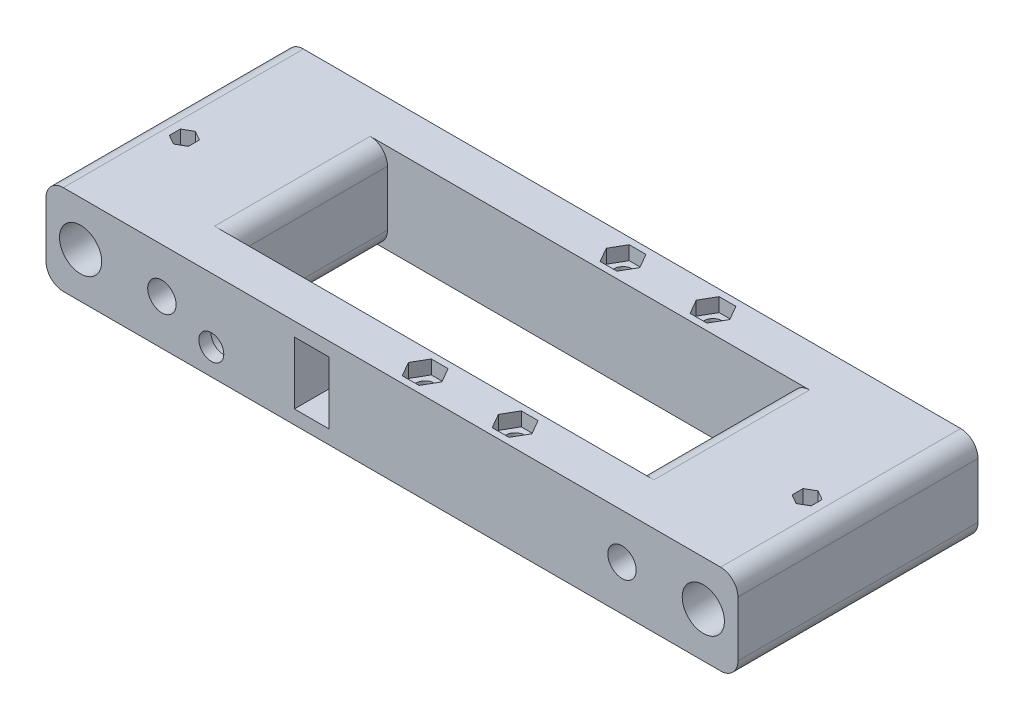
SolidWorks part; units mm, degrees
ref_plane "Front Plane" through (0, 0, 0) normal (0, 0, 1) x (1, 0, 0)
ref_plane "Top Plane" through (0, 0, 0) normal (0, 1, 0) x (1, 0, 0)
ref_plane "Right Plane" through (0, 0, 0) normal (1, 0, 0) x (0, 0, -1)
sketch "Sketch1" plane through (0, 0, 0) normal (0, 0, 1) x (1, 0, 0)
  line L0 (-58.5, 26) -> (-58.5, 0) construction
  line L1 (0, 0) -> (-100, 0)
  line L2 (0, 0) -> (0, 26)
  line L3 (0, 26) -> (-100, 26)
  line L4 (-100, 0) -> (-100, 26)
  circle A0 centre (-90, 13) radius 6.1
  circle A1 centre (-66.5, 13) radius 4.1
  point P9 (-100, 13)
  dimension "D3" = 12.2
  dimension "D4" = 8.2
  dimension "D1" = 100
  dimension "D2" = 26
  dimension "D5" = 23.5
  dimension "D6" = 10
  dimension "D7" = 8
  dimension "D8" = 41.5
extrude "Boss-Extrude1" add sketch "Sketch1" along normal blind 40
sketch "Sketch2" plane through (0, 0, 0) normal (0, 0, -1) x (-1, 0, 0)
  line L1 (100, 26) -> (0, 26)
  line L2 (100, 26) -> (100, 0)
  line L3 (100, 0) -> (0, 0)
  line L4 (0, 26) -> (0, 0)
extrude "Boss-Extrude2" add sketch "Sketch2" along normal blind 29.4
sketch "Sketch3" plane through (0, 26, 0) normal (0, 1, 0) x (1, 0, 0)
  line L0 (0, -40) -> (0, 29.4) construction
  line L1 (0, 17.2) -> (-58.5, 17.2)
  line L2 (0, 17.2) -> (0, -27.8)
  line L3 (0, -27.8) -> (-58.5, -27.8)
  line L4 (-58.5, 17.2) -> (-58.5, -27.8)
  line L5 (-100, -40) -> (-100, 29.4) construction
  line L6 (-100, 29.4) -> (0, 29.4) construction
  line L7 (0, -40) -> (-100, -40) construction
  dimension "D1" = 41.5
  dimension "D2" = 12.2
  dimension "D3" = 12.2
extrude "Cut-Extrude1" cut sketch "Sketch3" against normal up to next
mirror "Mirror2" about plane through (0, 0, 40) normal (-1, 0, 0) of "Boss-Extrude2", "Cut-Extrude1", "Boss-Extrude1"
sketch "Sketch4" plane through (0, 26, 0) normal (0, 1, 0) x (1, 0, 0)
  line L0 (-100, 29.4) -> (100, 29.4) construction
  line L1 (-5.5, 29.4) -> (-5.5, 17.2) construction
  line L2 (58.5, 17.2) -> (-58.5, 17.2) construction
  line L3 (58.5, 17.2) -> (58.5, -27.8) construction
  circle A0 centre (3.5, 23.3) radius 2.6
  circle A1 centre (29.5, 23.3) radius 2.6
  dimension "D1" = 6.1
  dimension "D3" = 9
  dimension "D4" = 26
  dimension "D5" = 5.2
  dimension "D2" = 64
extrude "Cut-Extrude2" cut sketch "Sketch4" against normal through all
sketch "Sketch5" plane through (0, 0, 0) normal (0, -1, 0) x (1, 0, 0)
  line L1 (34.2343, -23.3) -> (31.8671, -19.2)
  line L2 (31.8671, -19.2) -> (27.1329, -19.2)
  line L3 (27.1329, -19.2) -> (24.7657, -23.3)
  line L4 (24.7657, -23.3) -> (27.1329, -27.4)
  line L5 (27.1329, -27.4) -> (31.8671, -27.4)
  line L6 (31.8671, -27.4) -> (34.2343, -23.3)
  line L7 (-1.2343, -23.3) -> (1.1329, -27.4)
  line L8 (1.1329, -27.4) -> (5.8671, -27.4)
  line L9 (5.8671, -27.4) -> (8.2343, -23.3)
  line L10 (8.2343, -23.3) -> (5.8671, -19.2)
  line L11 (5.8671, -19.2) -> (1.1329, -19.2)
  line L12 (1.1329, -19.2) -> (-1.2343, -23.3)
  circle A0 centre (29.5, -23.3) radius 4.1 construction
  circle A1 centre (3.5, -23.3) radius 4.1 construction
  dimension "D1" = 8.2
  dimension "D2" = 8.2
extrude "Cut-Extrude3" cut sketch "Sketch5" against normal blind 4
ref_plane "Plane1" through (0, 0, 5.3) normal (0, 0, 1) x (1, 0, 0)
mirror "Mirror3" about plane through (0, 0, 5.3) normal (0, 0, 1) of "Cut-Extrude3", "Cut-Extrude2"
sketch "Sketch6" plane through (0, 0, 40) normal (0, 0, 1) x (1, 0, 0)
  line L0 (-8.1, 26) -> (-8.1, 0) construction
  line L1 (100, 26) -> (-100, 26) construction
  line L2 (-100, 0) -> (100, 0) construction
  line L3 (0.9, 26) -> (0.9, 4) construction
  line L4 (-100, 26) -> (-100, 0) construction
  line L5 (-18.2, 22) -> (-28.2, 22)
  line L6 (-18.2, 22) -> (-18.2, 4)
  line L7 (-18.2, 4) -> (-28.2, 4)
  line L8 (-28.2, 22) -> (-28.2, 4)
  point P12 (-28.2, 13)
  point P15 (-100, 13)
  dimension "D1" = 9
  dimension "D2" = 10.1
  dimension "D3" = 10
  dimension "D4" = 18
extrude "Cut-Extrude4" cut sketch "Sketch6" against normal up to vertex
fillet "Fillet1" radius 5 8 edges at (58.5, 26, 5.3) (58.5, 0, 5.3) (-58.5, 0, 5.3) (100, 0, 5.3) (100, 26, 5.3) (-100, 0, 5.3) (-100, 26, 5.3) (-58.5, 26, 5.3)
sketch "Sketch7" plane through (0, 26, 0) normal (0, 1, 0) x (1, 0, 0)
  line L0 (63.5, 17.2) -> (-63.5, 17.2) construction
  line L1 (8.3497, 23.3) -> (5.9249, 27.5)
  line L2 (5.9249, 27.5) -> (1.0751, 27.5)
  line L3 (1.0751, 27.5) -> (-1.3497, 23.3)
  line L4 (-1.3497, 23.3) -> (1.0751, 19.1)
  line L5 (1.0751, 19.1) -> (5.9249, 19.1)
  line L6 (5.9249, 19.1) -> (8.3497, 23.3)
  line L7 (34.3497, 23.3) -> (31.9249, 27.5)
  line L8 (31.9249, 27.5) -> (27.0751, 27.5)
  line L9 (27.0751, 27.5) -> (24.6503, 23.3)
  line L10 (24.6503, 23.3) -> (27.0751, 19.1)
  line L11 (27.0751, 19.1) -> (31.9249, 19.1)
  line L12 (31.9249, 19.1) -> (34.3497, 23.3)
  circle A0 centre (3.5, 23.3) radius 4.2 construction
  circle A1 centre (29.5, 23.3) radius 4.2 construction
  point P20 (29.5, 19.1)
  dimension "D1" = 8.4
  dimension "D2" = 8.4
extrude "Cut-Extrude5" cut sketch "Sketch7" against normal blind 4
mirror "Mirror4" about plane through (0, 0, 5.3) normal (0, 0, 1) of "Cut-Extrude5"
sketch "Sketch8" plane through (0, 4, 0) normal (0, -1, 0) x (1, 0, 0)
  line L0 (27.1329, 38) -> (31.8671, 38) construction
  line L1 (31.8671, 38) -> (34.2343, 33.9) construction
  line L2 (34.2343, 33.9) -> (31.8671, 29.8) construction
  line L3 (31.8671, 29.8) -> (27.1329, 29.8) construction
  line L4 (27.1329, 29.8) -> (24.7657, 33.9) construction
  line L5 (24.7657, 33.9) -> (27.1329, 38) construction
  line L6 (1.1329, 38) -> (5.8671, 38) construction
  line L7 (5.8671, 38) -> (8.2343, 33.9) construction
  line L8 (8.2343, 33.9) -> (5.8671, 29.8) construction
  line L9 (5.8671, 29.8) -> (1.1329, 29.8) construction
  line L10 (1.1329, 29.8) -> (-1.2343, 33.9) construction
  line L11 (-1.2343, 33.9) -> (1.1329, 38) construction
  line L12 (27.1329, 38) -> (31.8671, 38)
  line L13 (31.8671, 38) -> (34.2343, 33.9)
  line L14 (34.2343, 33.9) -> (31.8671, 29.8)
  line L15 (31.8671, 29.8) -> (27.1329, 29.8)
  line L16 (27.1329, 29.8) -> (24.7657, 33.9)
  line L17 (24.7657, 33.9) -> (27.1329, 38)
  line L18 (1.1329, 38) -> (5.8671, 38)
  line L19 (5.8671, 38) -> (8.2343, 33.9)
  line L20 (8.2343, 33.9) -> (5.8671, 29.8)
  line L21 (5.8671, 29.8) -> (1.1329, 29.8)
  line L22 (1.1329, 29.8) -> (-1.2343, 33.9)
  line L23 (-1.2343, 33.9) -> (1.1329, 38)
  circle A0 centre (3.5, 33.9) radius 2.6 construction
  circle A1 centre (29.5, 33.9) radius 2.6 construction
  circle A2 centre (3.5, 33.9) radius 2.6
  circle A3 centre (29.5, 33.9) radius 2.6
extrude "Boss-Extrude3" add sketch "Sketch8" along normal up to surface (4 mm away) up to face at (3.5, 0, 33.9)
sketch "Sketch9" plane through (0, 4, 0) normal (0, -1, 0) x (1, 0, 0)
  line L0 (31.8671, -19.2) -> (27.1329, -19.2) construction
  line L1 (34.2343, -23.3) -> (31.8671, -19.2) construction
  line L2 (31.8671, -27.4) -> (34.2343, -23.3) construction
  line L3 (27.1329, -27.4) -> (31.8671, -27.4) construction
  line L4 (24.7657, -23.3) -> (27.1329, -27.4) construction
  line L5 (27.1329, -19.2) -> (24.7657, -23.3) construction
  line L6 (1.1329, -19.2) -> (-1.2343, -23.3) construction
  line L7 (5.8671, -19.2) -> (1.1329, -19.2) construction
  line L8 (8.2343, -23.3) -> (5.8671, -19.2) construction
  line L9 (5.8671, -27.4) -> (8.2343, -23.3) construction
  line L10 (1.1329, -27.4) -> (5.8671, -27.4) construction
  line L11 (-1.2343, -23.3) -> (1.1329, -27.4) construction
  line L12 (31.8671, -19.2) -> (27.1329, -19.2)
  line L13 (34.2343, -23.3) -> (31.8671, -19.2)
  line L14 (31.8671, -27.4) -> (34.2343, -23.3)
  line L15 (27.1329, -27.4) -> (31.8671, -27.4)
  line L16 (24.7657, -23.3) -> (27.1329, -27.4)
  line L17 (27.1329, -19.2) -> (24.7657, -23.3)
  line L18 (1.1329, -19.2) -> (-1.2343, -23.3)
  line L19 (5.8671, -19.2) -> (1.1329, -19.2)
  line L20 (8.2343, -23.3) -> (5.8671, -19.2)
  line L21 (5.8671, -27.4) -> (8.2343, -23.3)
  line L22 (1.1329, -27.4) -> (5.8671, -27.4)
  line L23 (-1.2343, -23.3) -> (1.1329, -27.4)
  circle A0 centre (3.5, -23.3) radius 2.6 construction
  circle A1 centre (29.5, -23.3) radius 2.6 construction
  circle A2 centre (3.5, -23.3) radius 2.6
  circle A3 centre (29.5, -23.3) radius 2.6
extrude "Boss-Extrude4" add sketch "Sketch9" along normal up to surface (4 mm away) up to face at (29.5, 0, -23.3)
sketch "Sketch10" plane through (0, 0, 0) normal (0, -1, 0) x (1, 0, 0)
  line L1 (-96.1, 0) -> (-83.9, 0) construction
  line L2 (83.9, 0) -> (96.1, 0) construction
  circle A0 centre (-90, 10) radius 1.5
  circle A1 centre (90, 10) radius 1.5
  point P5 (-90, 0)
  point P14 (90, 0)
  dimension "D3" = 3
  dimension "D4" = 3
  dimension "D1" = 10
  dimension "D2" = 10
extrude "Cut-Extrude6" cut sketch "Sketch10" against normal through all
sketch "Sketch11" plane through (0, 26, 0) normal (0, 1, 0) x (1, 0, 0)
  line L0 (-95, 29.4) -> (-95, -40) construction
  line L1 (-90, -13.1754) -> (-87.25, -11.5877)
  line L2 (-87.25, -11.5877) -> (-87.25, -8.4123)
  line L3 (-87.25, -8.4123) -> (-90, -6.8246)
  line L4 (-90, -6.8246) -> (-92.75, -8.4123)
  line L5 (-92.75, -8.4123) -> (-92.75, -11.5877)
  line L6 (-92.75, -11.5877) -> (-90, -13.1754)
  line L7 (90, -13.1754) -> (92.75, -11.5877)
  line L8 (92.75, -11.5877) -> (92.75, -8.4123)
  line L9 (92.75, -8.4123) -> (90, -6.8246)
  line L10 (90, -6.8246) -> (87.25, -8.4123)
  line L11 (87.25, -8.4123) -> (87.25, -11.5877)
  line L12 (87.25, -11.5877) -> (90, -13.1754)
  line L13 (95, -40) -> (95, 29.4) construction
  circle A0 centre (-90, -10) radius 2.75 construction
  circle A1 centre (90, -10) radius 2.75 construction
  point P10 (92.75, -10)
  dimension "D1" = 5.5
  dimension "D2" = 5.5
extrude "Cut-Extrude7" cut sketch "Sketch11" against normal blind 4
hole_wizard "Hole1" positions "3DSketch1" profile "Sketch12" legacy
sketch3d "3DSketch1"
  line L0 (-58.5, 5, 27.8) -> (-58.5, 21, 27.8) construction
  line L1 (63.5, 0, 27.8) -> (-63.5, 0, 27.8) construction
  point P0 (-52.21, 7.5, 27.8)
  dimension "D1" = 6.29
  dimension "D2" = 7.5
sketch "Sketch12" plane through (-52.21, 7.5, 27.8) normal (1, 0, 0) x (0, 1, 0)
  line L0 (0, 0) -> (0, 12.2)
  line L1 (0, 12.2) -> (3.6, 12.2)
  line L2 (3.6, 12.2) -> (3.6, 8.7)
  line L3 (3.6, 8.7) -> (5, 8.7)
  line L4 (5, 8.7) -> (5, 0)
  line L5 (5, 0) -> (0, 0)
  line L6 (0, 110) -> (0, -10) construction
  dimension "Diameter" = 7.2
  dimension "Depth" = 12.2
  dimension "C-Bore Diameter" = 10
  dimension "C-Bore Depth" = 8.7
